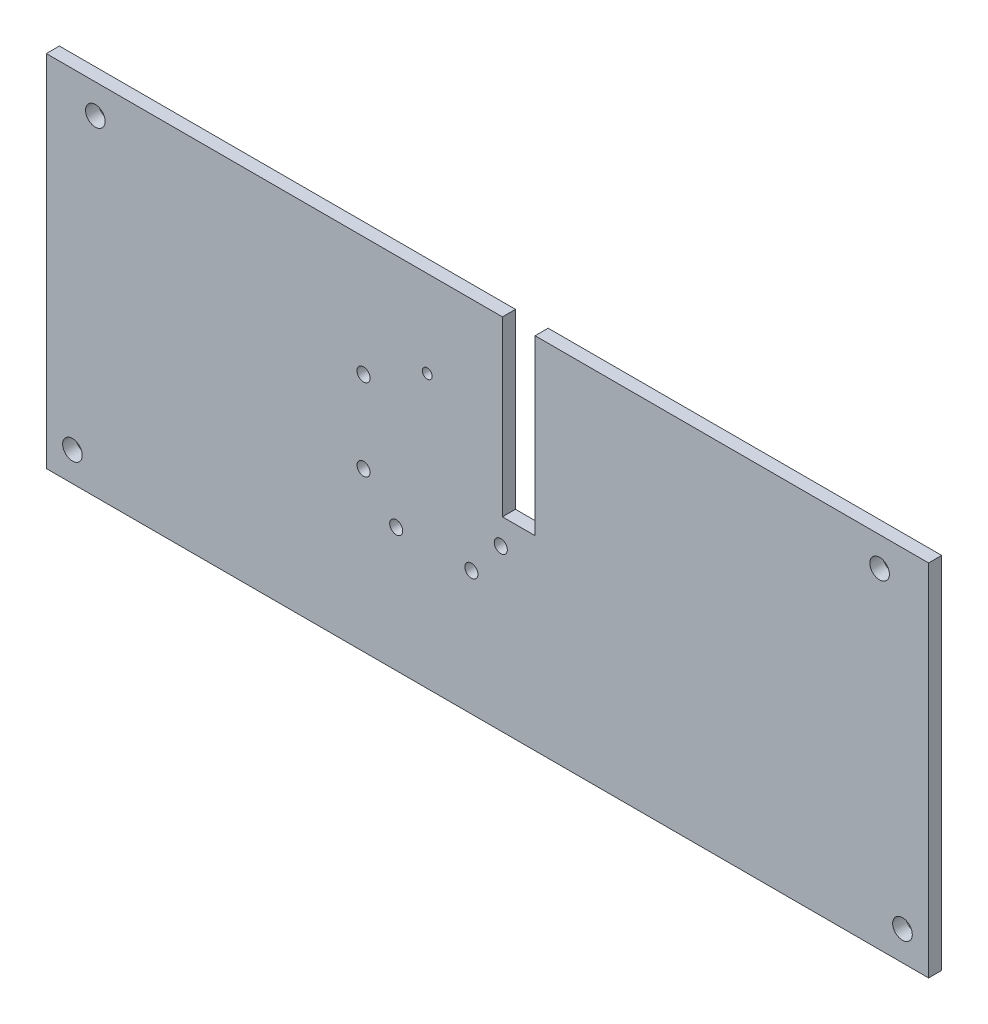
SolidWorks part; units mm, degrees
ref_plane "Front Plane" through (0, 0, 0) normal (0, 0, 1) x (1, 0, 0)
ref_plane "Top Plane" through (0, 0, 0) normal (0, 1, 0) x (1, 0, 0)
ref_plane "Right Plane" through (0, 0, 0) normal (1, 0, 0) x (0, 0, -1)
sketch "Sketch1" plane through (0, 0, 0) normal (0, 0, 1) x (1, 0, 0)
  line L1 (135, 55) -> (-135, 55)
  line L2 (135, 55) -> (135, -55)
  line L3 (135, -55) -> (-135, -55)
  line L4 (-135, 55) -> (-135, -55)
  line L5 (135, 55) -> (-135, -55) construction
  line L6 (135, -55) -> (-135, 55) construction
  point P0 (0, 0)
  dimension "D1" = 270
  dimension "D2" = 110
extrude "Boss-Extrude1" add sketch "Sketch1" along normal blind 4
sketch "Sketch9" plane through (0, 0, 0) normal (0, 0, -1) x (-1, 0, 0)
  line L0 (-6.5745, 5.0071) -> (-6.5745, 25) construction
  line L1 (-10.5745, 25) -> (-10.5745, 5.0071) construction
  line L2 (-6.5745, 5.0071) -> (-6.5745, 25) construction
  line L3 (-10.5745, 25) -> (-10.5745, 5.0071) construction
  line L4 (-4.5745, 2.0071) -> (-14.5745, 2.0071)
  line L5 (-14.5745, 2.0071) -> (-14.5745, 55)
  line L6 (-135, 55) -> (135, 55) construction
  line L7 (-14.5745, 55) -> (-4.5745, 55)
  line L8 (-4.5745, 55) -> (-4.5745, 2.0071)
  circle A0 centre (-120, 46) radius 3 construction
  circle A1 centre (-127, -46) radius 3 construction
  circle A2 centre (120, 46) radius 3 construction
  circle A3 centre (127, -46) radius 3 construction
  circle A4 centre (-4.0745, -6) radius 2 construction
  circle A5 centre (4.9255, -17) radius 2 construction
  circle A6 centre (27.9255, -17) radius 2 construction
  circle A7 centre (37.9255, -6.5) radius 2 construction
  circle A8 centre (37.9255, 18.5) radius 2 construction
  circle A9 centre (18.4255, 28.5) radius 1.5 construction
  circle A10 centre (-120, 46) radius 3
  circle A11 centre (-127, -46) radius 3
  circle A12 centre (120, 46) radius 3
  circle A13 centre (127, -46) radius 3
  circle A14 centre (-4.0745, -6) radius 2
  circle A15 centre (4.9255, -17) radius 2
  circle A16 centre (27.9255, -17) radius 2
  circle A17 centre (37.9255, -6.5) radius 2
  circle A18 centre (37.9255, 18.5) radius 2
  circle A19 centre (18.4255, 28.5) radius 1.5
  dimension "D1" = 4
  dimension "D2" = 4
  dimension "D3" = 3
extrude "Cut-Extrude1" cut sketch "Sketch9" against normal through all
